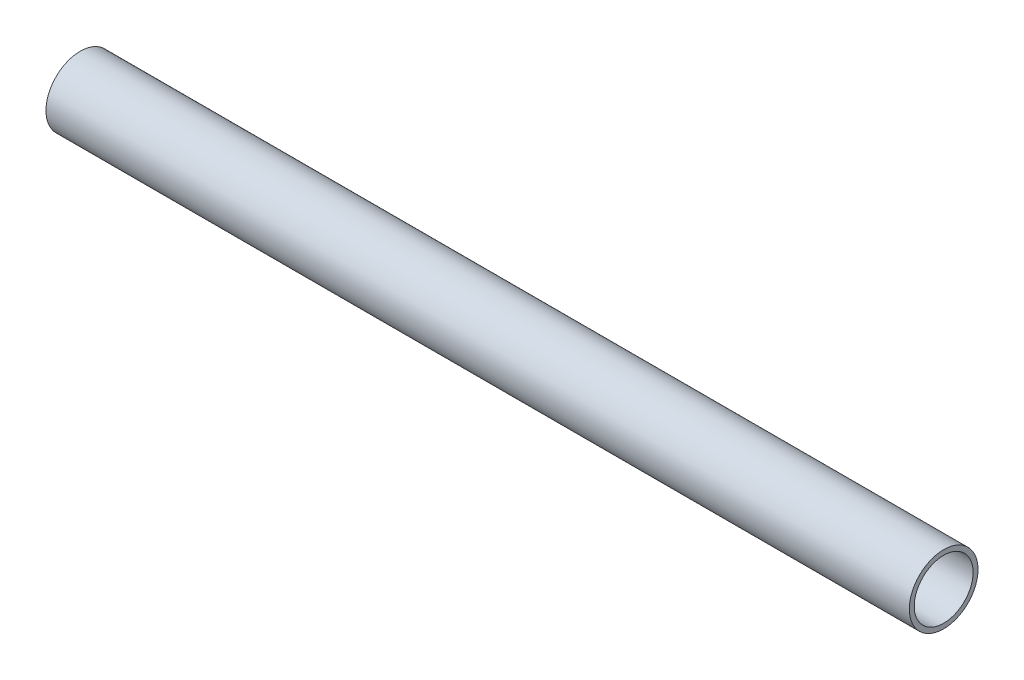
SolidWorks part; units mm, degrees
material "Zoltek Panex 33"
ref_plane "Front Plane" through (0, 0, 0) normal (0, 0, 1) x (1, 0, 0)
ref_plane "Top Plane" through (0, 0, 0) normal (0, 1, 0) x (1, 0, 0)
ref_plane "Right Plane" through (0, 0, 0) normal (1, 0, 0) x (0, 0, -1)
sketch "Sketch1" plane through (0, 0, 0) normal (1, 0, 0) x (0, 0, -1)
  circle A0 centre (0, 0) radius 11.1125
  circle A1 centre (0, 0) radius 9.525
  dimension "D1" = 22.225
  dimension "D2" = 19.05
extrude "Boss-Extrude1" add sketch "Sketch1" along normal mid plane 279.4
